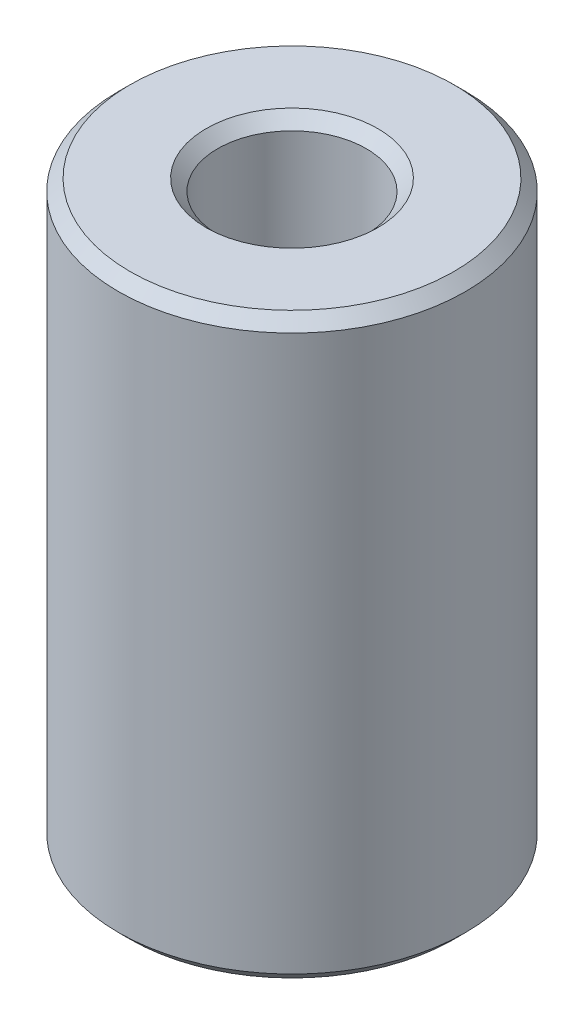
SolidWorks part; units mm, degrees
ref_plane "Front Plane" through (0, 0, 0) normal (0, 0, 1) x (1, 0, 0)
ref_plane "Top Plane" through (0, 0, 0) normal (0, 1, 0) x (1, 0, 0)
ref_plane "Right Plane" through (0, 0, 0) normal (1, 0, 0) x (0, 0, -1)
sketch "Sketch1" plane through (0, 0, 0) normal (0, 1, 0) x (1, 0, 0)
  circle A0 centre (0, 0) radius 3.81
  dimension "D1" = 7.62
extrude "Boss-Extrude1" add sketch "Sketch1" against normal blind 12.7
hole_wizard "#30 (0.1285) Diameter Hole1" positions "Sketch2" profile "Sketch3" hole size "#30" standard "ANSI Inch" end condition through all
sketch "Sketch2" plane through (0, 0, 0) normal (0, 1, 0) x (1, 0, 0)
  point P0 (0, 0)
sketch "Sketch3" plane through (0, 0, 0) normal (1, 0, 0) x (0, 0, 1)
  line L0 (0, 0) -> (0, 12.7)
  line L1 (0, 12.7) -> (1.6319, 12.7)
  line L2 (1.6319, 12.7) -> (1.6319, 0)
  line L5 (1.6319, 0) -> (0, 0)
  line L11 (0, -6.35) -> (0, 107.95) construction
  dimension "Thru Hole Dia." = 3.2639
  dimension "Thru Hole Depth" = 12.7
chamfer "Chamfer1" distance 0.254 angle 45 4 edges at (0, -12.7, 3.81) (0, -12.7, 1.6319) (0, 0, 3.81) (0, 0, 1.6319)
